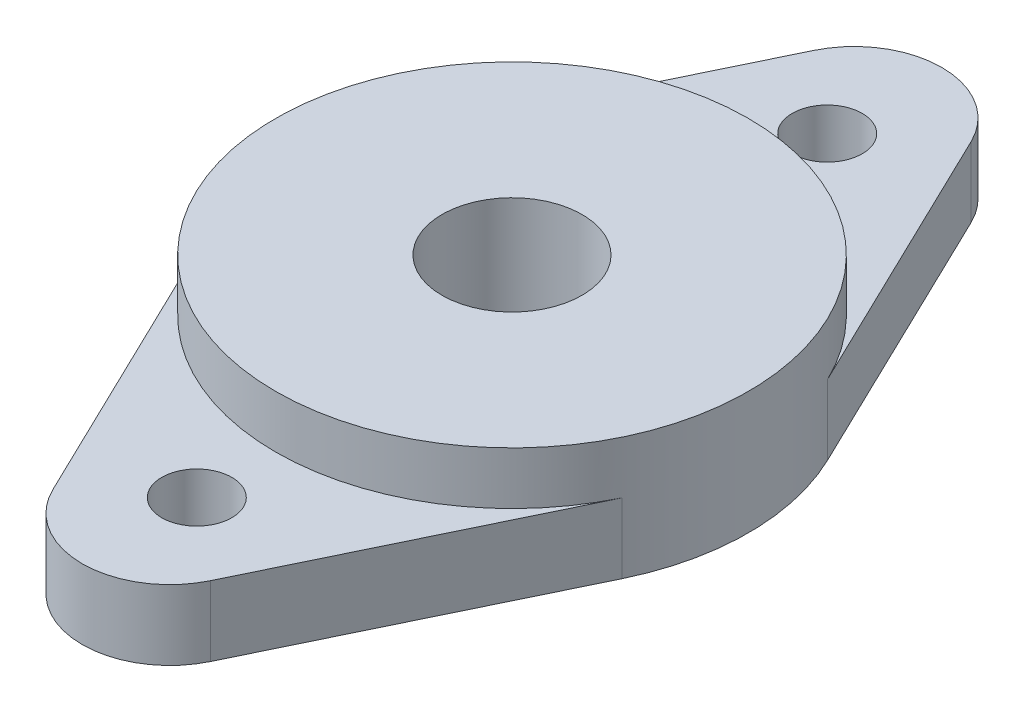
SolidWorks part; units mm, degrees
ref_plane "Front Plane" through (0, 0, 0) normal (0, 0, 1) x (1, 0, 0)
ref_plane "Top Plane" through (0, 0, 0) normal (0, 1, 0) x (1, 0, 0)
ref_plane "Right Plane" through (0, 0, 0) normal (1, 0, 0) x (0, 0, -1)
sketch "Sketch1" plane through (0, 0, 0) normal (0, 1, 0) x (1, 0, 0)
  line L0 (12.1564, 5.8712) -> (4.5024, 21.7191)
  line L1 (-4.5024, 21.7191) -> (-12.1564, 5.8712)
  line L2 (-33.2776, 0) -> (29.2439, 0) construction
  line L3 (-4.5024, -21.7191) -> (-12.1564, -5.8712)
  line L4 (12.1564, -5.8712) -> (4.5024, -21.7191)
  circle A0 centre (0, 0) radius 13.5
  arc A1 (4.5024, 21.7191) -> (-4.5024, 21.7191) centre (0, 19.5445) ccw
  arc A2 (4.5024, -21.7191) -> (-4.5024, -21.7191) centre (0, -19.5445) cw
  arc A3 (-12.1564, 5.8712) -> (12.1564, 5.8712) centre (0, 0) cw
  arc A4 (12.1564, -5.8712) -> (-12.1564, -5.8712) centre (0, 0) cw
  point P17 (0, 24.5445)
  point P18 (0, -24.5445)
  dimension "D1" = 27
  dimension "D2" = 5
extrude "Boss-Extrude1" add sketch "Sketch1" along normal blind 4 contours L2 A0 | A0 L2 | L0 A1 L1 A0 | A2 L4 A0 L3
sketch "Sketch2" plane through (0, 4, 0) normal (0, 1, 0) x (1, 0, 0)
  line L0 (12.1564, 5.8712) -> (4.5024, 21.7191) construction
  circle A0 centre (0, -18) radius 2
  circle A1 centre (0, 18) radius 2
  point P4 (0, 0)
  dimension "D1" = 4
  dimension "D2" = 18
  dimension "D3" = 18
  dimension "D4" = 5.6717
extrude "Cut-Extrude1" cut sketch "Sketch2" against normal through all
sketch "Sketch3" plane through (0, 4, 0) normal (0, 1, 0) x (1, 0, 0)
  circle A0 centre (0, 0) radius 13.5
  dimension "D1" = 27
extrude "Boss-Extrude2" add sketch "Sketch3" along normal blind 3
sketch "Sketch4" plane through (0, 7, 0) normal (0, 1, 0) x (1, 0, 0)
  circle A0 centre (0, 0) radius 4
  dimension "D1" = 8
extrude "Cut-Extrude2" cut sketch "Sketch4" against normal through all
